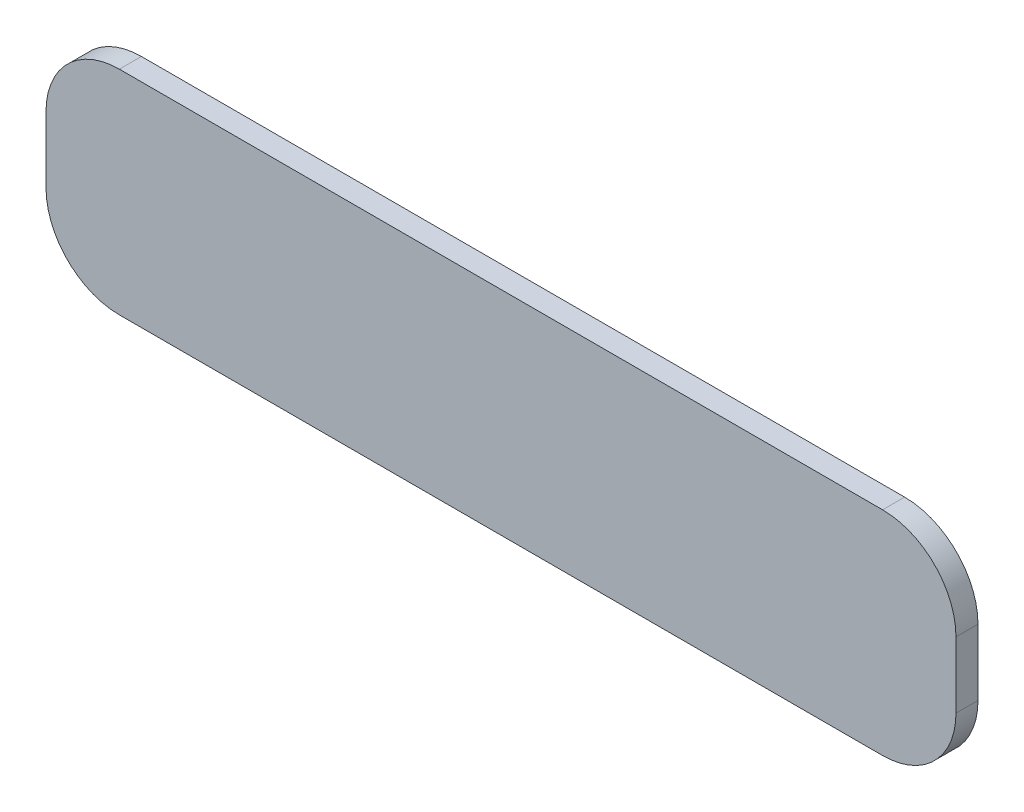
SolidWorks part; units mm, degrees
ref_plane "Alzado" through (0, 0, 0) normal (0, 0, 1) x (1, 0, 0)
ref_plane "Planta" through (0, 0, 0) normal (0, 1, 0) x (1, 0, 0)
ref_plane "Vista lateral" through (0, 0, 0) normal (1, 0, 0) x (0, 0, -1)
sketch "Croquis1" plane through (0, 0, 0) normal (0, 0, 1) x (1, 0, 0)
  line L1 (-62, 14.5) -> (62, 14.5)
  line L2 (-62, 14.5) -> (-62, -14.5)
  line L3 (-62, -14.5) -> (62, -14.5)
  line L4 (62, 14.5) -> (62, -14.5)
  dimension "D1" = 124
  dimension "D2" = 62
  dimension "D3" = 29
  dimension "D4" = 14.5
extrude "Saliente-Extruir1" add sketch "Croquis1" along normal blind 3
fillet "Redondeo1" radius 10 4 edges at (62, 14.5, 1.5) (62, -14.5, 1.5) (-62, -14.5, 1.5) (-62, 14.5, 1.5)
